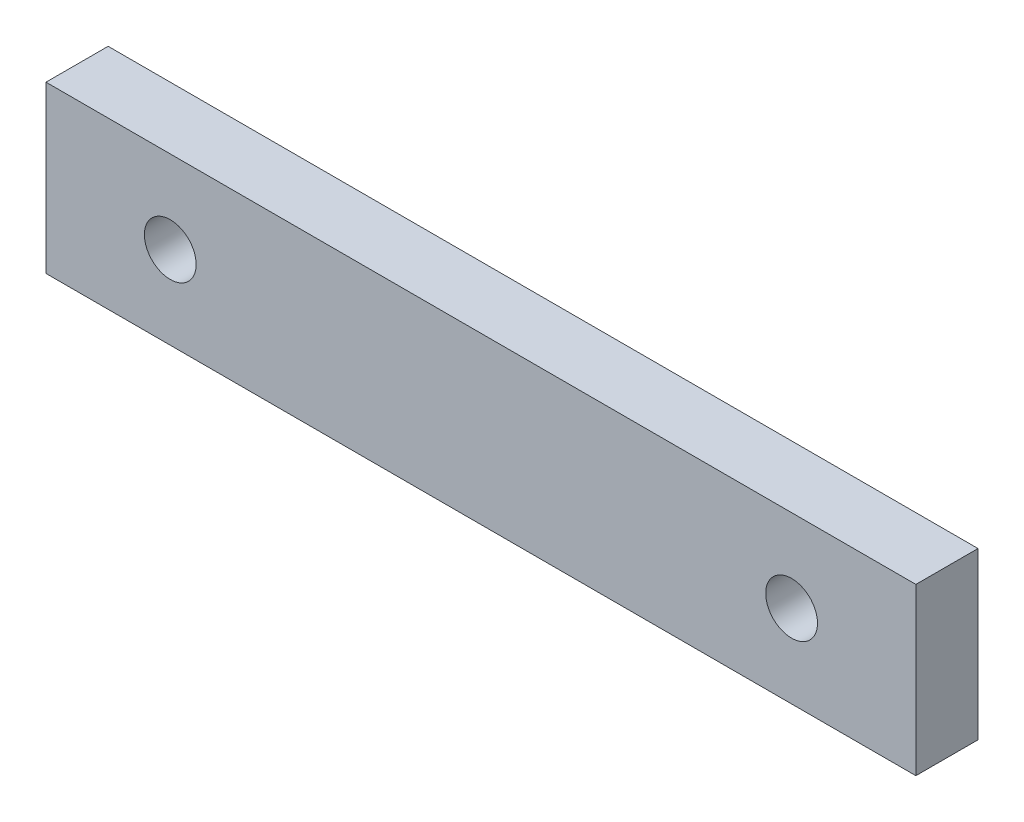
SolidWorks part; units mm, degrees
ref_plane "Front Plane" through (0, 0, 0) normal (0, 0, 1) x (1, 0, 0)
ref_plane "Top Plane" through (0, 0, 0) normal (0, 1, 0) x (1, 0, 0)
ref_plane "Right Plane" through (0, 0, 0) normal (1, 0, 0) x (0, 0, -1)
sketch "Sketch1" plane through (0, 0, 0) normal (0, 0, 1) x (1, 0, 0)
  line L1 (0, 0) -> (210, 0)
  line L2 (0, 0) -> (0, 40)
  line L3 (0, 40) -> (210, 40)
  line L4 (210, 0) -> (210, 40)
extrude "Boss-Extrude1" add sketch "Sketch1" along normal blind 15 contours L2 L3 L4 L1
sketch "Sketch2" plane through (0, 0, 15) normal (0, 0, 1) x (1, 0, 0)
  line L0 (0, 20) -> (30, 20) construction
  line L1 (0, 0) -> (0, 40) construction
  line L2 (210, 20) -> (180, 20) construction
  line L3 (210, 0) -> (210, 40) construction
  circle A0 centre (30, 20) radius 6.25
  circle A1 centre (180, 20) radius 6.25
  dimension "D1" = 12.5
  dimension "D2" = 12.5
extrude "Cut-Extrude1" cut sketch "Sketch2" against normal blind 15
